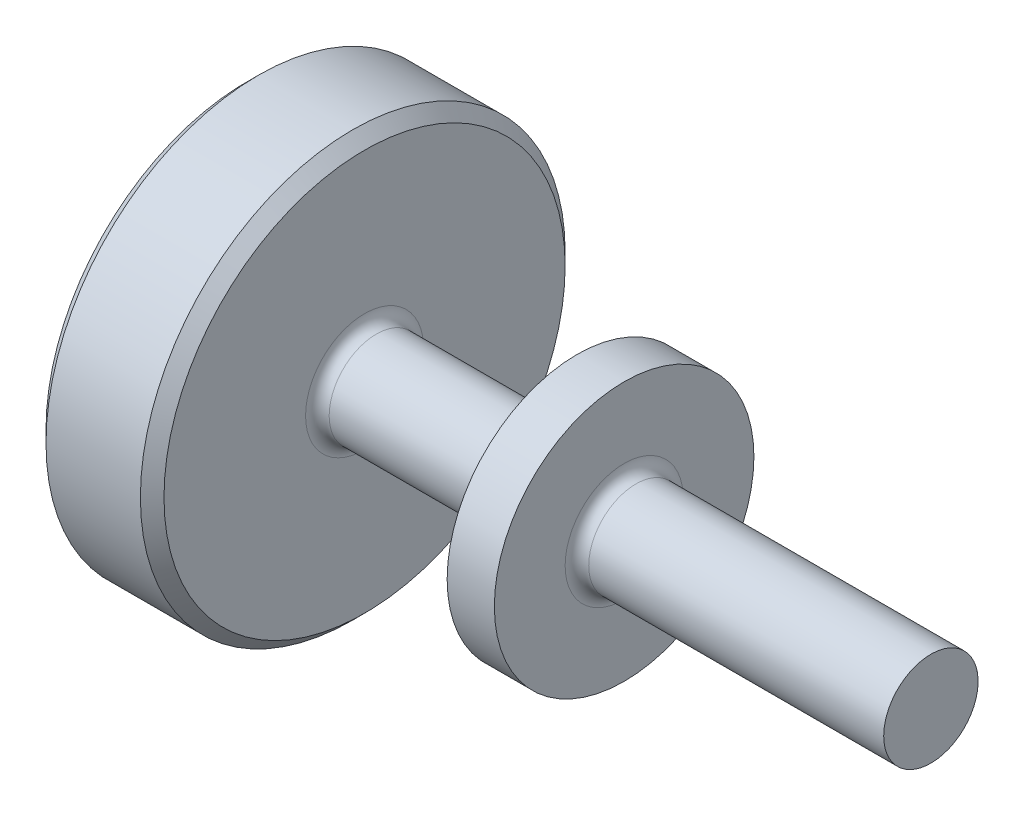
SolidWorks part; units mm, degrees
material "AISI 1035 Steel (SS)"
ref_plane "Front Plane" through (0, 0, 0) normal (0, 0, 1) x (1, 0, 0)
ref_plane "Top Plane" through (0, 0, 0) normal (0, 1, 0) x (1, 0, 0)
ref_plane "Right Plane" through (0, 0, 0) normal (1, 0, 0) x (0, 0, -1)
sketch "Sketch1" plane through (0, 0, 0) normal (0, 0, 1) x (1, 0, 0)
  line L0 (0, 0) -> (61.5717, 0) construction
  line L1 (0, 0) -> (0, 18)
  line L2 (0, 18) -> (10, 18)
  line L3 (10, 18) -> (10, 4)
  line L4 (10, 4) -> (28, 4)
  line L5 (28, 4) -> (28, 11)
  line L6 (28, 11) -> (32, 11)
  line L7 (32, 11) -> (32, 4)
  line L8 (32, 4) -> (58, 4)
  line L9 (58, 4) -> (58, 0)
  line L10 (58, 0) -> (0, 0)
  point P4 (58, 2)
  dimension "D1" = 8
  dimension "D2" = 22
  dimension "D3" = 36
  dimension "D4" = 8
  dimension "D5" = 58
  dimension "D6" = 10
  dimension "D7" = 26
  dimension "D8" = 4
revolve "Revolve1" add sketch "Sketch1" angle 360 about L0
cosmetic thread "Cosmetic Thread1" parameters "D1"=22, "D2"=6.619
chamfer "Chamfer1" distance 1 angle 45 2 edges at (10, 0, 18) (0, 0, 18)
fillet "Fillet1" radius 1 3 edges at (32, 0, 4) (28, 0, 4) (10, 0, 4)
